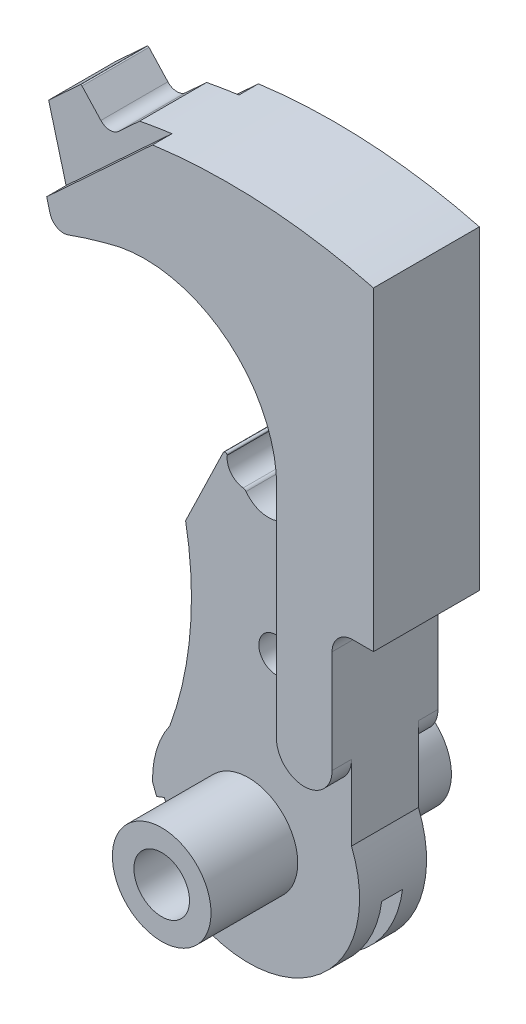
SolidWorks part; units mm, degrees
ref_plane "Front Plane" through (0, 0, 0) normal (0, 0, 1) x (1, 0, 0)
ref_plane "Top Plane" through (0, 0, 0) normal (0, 1, 0) x (1, 0, 0)
ref_plane "Right Plane" through (0, 0, 0) normal (1, 0, 0) x (0, 0, -1)
sketch "Sketch1" plane through (0, 0, 0) normal (0, 0, 1) x (1, 0, 0)
  line L0 (0, 0) -> (-5.4824, 9.4958) construction
  line L1 (0, 0) -> (0, 5.9391)
  line L2 (-5.5315, -2.1233) -> (-7.42, -2.8483)
  line L3 (8, 0) -> (-6.9, 0)
  line L4 (7.42, 9.3953) -> (4.3096, 9.3953)
  line L5 (-5.4824, 9.4958) -> (-12.2807, 5.5708)
  line L6 (0, 0) -> (64.7351, 0) construction
  line L7 (0, 0) -> (-6.9, 0) construction
  line L8 (-12.2807, 5.5708) -> (-7.42, -2.8483) construction
  line L9 (-6.898, -0.168) -> (-6.6058, -0.929)
  line L10 (-7.42, -2.8483) -> (-6.0273, -5.2603)
  line L11 (-6.069, -0.723) -> (-6.6058, -0.929)
  line L12 (-29.5, 0) -> (-29.5, 12.7) construction
  line L13 (-12.463, 0) -> (-29.5, 0) construction
  line L14 (3.439, 22.4832) -> (3.439, 24.0389)
  line L15 (0, 0) -> (55.9226, 51.6581) construction
  line L16 (10.4, 17.3) -> (8.92, 17.3)
  line L17 (-14.3773, 38.5869) -> (-12.8729, 32.9724)
  line L18 (-9.8884, 42.7335) -> (-9.8884, 42.7335)
  line L19 (-6.0367, -0.7373) -> (-5.5171, -2.091)
  line L20 (0, 21.4277) -> (0, 58.1236) construction
  line L21 (76.0334, 0) -> (76.0334, 23)
  line L22 (76.0334, 23) -> (-18.3142, 23) construction
  line L23 (0, -18.7657) -> (0, 8) construction
  line L24 (-28.2689, 25.7547) -> (-25.8525, 27.9867)
  line L25 (10.4, 39.9691) -> (10.4, 17.3)
  line L26 (-39.1696, 36.6554) -> (-18.3142, 15.8)
  line L27 (-9.8884, 42.7335) -> (30.07, 79.6448) construction
  line L28 (-1.8081, 22.9153) -> (-20.4385, -15.63)
  line L29 (7.42, 15.8) -> (7.42, 2.9906)
  line L30 (-1.5211, 22.8792) -> (-1.5371, 22.9134)
  line L31 (-8.4076, 40.0172) -> (-8.4076, 40.0172)
  line L32 (-9.3461, 39.1504) -> (-7.8298, 40.551)
  line L33 (-4.7807, 6.8592) -> (-8.9771, 5.2484)
  line L34 (-7.7738, 38.833) -> (-7.7738, 38.833)
  line L35 (-24.9138, 23) -> (-22.9348, 24.8281)
  line L36 (-8.4076, 40.0172) -> (32.1057, 77.4411) construction
  line L37 (-7.7738, 38.833) -> (32.9878, 76.4862) construction
  line L38 (0, 0) -> (-59.4391, 64.3459) construction
  line L39 (2.9572, 24.505) -> (2.9572, 24.505)
  line L40 (-10.6179, 39.2008) -> (-11.975, 40.6699)
  line L41 (2.9572, 24.505) -> (-45.6294, 77.1025) construction
  line L42 (-14.3773, 38.5869) -> (-12.1163, 40.6755)
  line L43 (182.9929, 126.3651) -> (184.9037, 27.9867)
  arc A0 (-6.0273, -5.2603) -> (7.42, 2.9906) centre (0, 0) ccw
  arc A2 (-5.6516, 3.9584) -> (-4.5206, 17.3032) centre (-29.5, 12.7) ccw
  arc A3 (-5.5315, -2.1233) -> (-5.5171, -2.091) centre (-5.5404, -2.1) ccw
  arc A4 (-6.0367, -0.7373) -> (-6.069, -0.723) centre (-6.0601, -0.7463) ccw
  circle A5 centre (0, 0) radius 2
  arc A6 (-1.5371, 22.9134) -> (-1.8081, 22.9153) centre (-1.673, 22.85) ccw
  arc A8 (-10.6179, 39.2008) -> (-9.3461, 39.1504) centre (-9.9568, 39.8115) ccw
  arc A9 (8.92, 17.3) -> (7.42, 15.8) centre (8.92, 15.8) ccw
  arc A10 (10.4, 39.9691) -> (-7.8298, 40.551) centre (0, 0) ccw
  arc A11 (-7.8825, 33.382) -> (-11.5697, 32.2898) centre (0, 0) ccw
  circle A12 centre (-58.0443, 40.974) radius 9.5
  circle A13 centre (-46.7362, 30.9955) radius 2
  arc A16 (3.439, 24.0389) -> (-7.8825, 33.382) centre (-6.061, 24.0582) ccw
  arc A18 (-1.4991, 23) -> (-0.3776, 21.4148) centre (-0.2326, 22.7067) ccw
  arc A19 (-0.1697, 21.2949) -> (3.439, 22.4832) centre (1.439, 22.4832) ccw
  arc A20 (-0.3776, 21.4148) -> (-0.1697, 21.2949) centre (-0.411, 21.1166) cw
  arc A21 (-11.975, 40.6699) -> (-12.1163, 40.6755) centre (-12.0484, 40.602) ccw
  arc A22 (-5.6516, 3.9584) -> (-6.898, -0.168) centre (0, 0) ccw
  arc A23 (-11.5697, 32.2898) -> (-12.8729, 32.9724) centre (-11.907, 33.2312) cw
  circle A24 centre (163.4559, 87.388) radius 20.2902
  point P48 (-1.553, 23.4431)
  dimension "D1" = 16
  dimension "D8" = 9.3953
  dimension "D12" = 23
  dimension "D10" = 0.025
  dimension "D16" = 0.3
  dimension "D17" = 7.42
  dimension "D15" = 1.5
  dimension "D18" = 34.3
  dimension "D19" = 41.3
  dimension "D24" = 25
  dimension "D25" = 2.6
  dimension "D26" = 0.3
  dimension "D4" = 17.3
  dimension "D9" = 9.5
  dimension "D30" = 0.9
  dimension "D31" = 0.1
  dimension "D32" = 1
  dimension "D2" = 30
  dimension "D3" = 21
  dimension "D5" = 7.85
  dimension "D6" = 17.3
  dimension "D7" = 1.5
  dimension "D11" = 12.7
  dimension "D13" = 0.6
  dimension "D14" = 10.4
  dimension "D20" = 15
  dimension "D21" = 42.73
  dimension "D23" = 35.1
  dimension "D28" = 90
  dimension "D22" = 38.1
  dimension "D27" = 33.8
  dimension "D29" = 18.8
sketch "Sketch6" plane through (0, 0, 0) normal (0, 0, 1) x (1, 0, 0)
  circle A1 centre (2, 12.2) radius 1.25
  dimension "D3" = 2
  dimension "D1" = 2.5
  dimension "D2" = 12.2
sketch "Sketch10" plane through (0, 0, 0) normal (0, 1, 0) x (1, 0, 0)
  circle A0 centre (2, 0) radius 1.5
  dimension "D1" = 2
extrude "Boss-Extrude2" add sketch "Sketch1" along normal mid plane 17.3
ref_plane "Plane1" through (0, 0, 8.65) normal (0, 0, 1) x (1, 0, 0)
sketch "Sketch18" plane through (0, 0, 8.65) normal (0, 0, 1) x (1, 0, 0)
  line L0 (0, 0) -> (-5.4824, 9.4958) construction
  line L1 (0, 0) -> (0, 5.9391)
  line L2 (-5.5315, -2.1233) -> (-7.42, -2.8483)
  line L3 (8, 0) -> (-6.9, 0)
  line L4 (7.42, 9.3953) -> (4.3096, 9.3953)
  line L5 (-5.4824, 9.4958) -> (-12.2807, 5.5708)
  line L6 (0, 0) -> (64.7351, 0) construction
  line L7 (0, 0) -> (-6.9, 0) construction
  line L8 (-12.2807, 5.5708) -> (-7.42, -2.8483) construction
  line L9 (-6.898, -0.168) -> (-6.6058, -0.929)
  line L10 (-7.42, -2.8483) -> (-6.0273, -5.2603)
  line L11 (-6.069, -0.723) -> (-6.6058, -0.929)
  line L12 (-29.5, 0) -> (-29.5, 12.7) construction
  line L13 (-12.463, 0) -> (-29.5, 0) construction
  line L14 (3.439, 22.4832) -> (3.439, 24.0389)
  line L15 (0, 0) -> (55.9226, 51.6581) construction
  line L16 (10.4, 17.3) -> (8.92, 17.3)
  line L17 (-14.3773, 38.5869) -> (-12.8729, 32.9724)
  line L18 (-9.8884, 42.7335) -> (-9.8884, 42.7335)
  line L19 (-6.0367, -0.7373) -> (-5.5171, -2.091)
  line L20 (0, 21.4277) -> (0, 58.1236) construction
  line L21 (76.0334, 0) -> (76.0334, 23)
  line L22 (76.0334, 23) -> (-18.3142, 23) construction
  line L23 (0, -18.7657) -> (0, 8) construction
  line L24 (-28.2689, 25.7547) -> (-25.8525, 27.9867)
  line L25 (10.4, 39.9691) -> (10.4, 17.3)
  line L26 (-39.1696, 36.6554) -> (-18.3142, 15.8)
  line L27 (-9.8884, 42.7335) -> (30.07, 79.6448) construction
  line L28 (-1.8081, 22.9153) -> (-20.4385, -15.63)
  line L29 (7.42, 15.8) -> (7.42, 2.9906)
  line L30 (-1.5211, 22.8792) -> (-1.5371, 22.9134)
  line L31 (-8.4076, 40.0172) -> (-8.4076, 40.0172)
  line L32 (-9.3461, 39.1504) -> (-7.8298, 40.551)
  line L33 (-4.7807, 6.8592) -> (-8.9771, 5.2484)
  line L34 (-7.7738, 38.833) -> (-7.7738, 38.833)
  line L35 (-24.9138, 23) -> (-22.9348, 24.8281)
  line L36 (-8.4076, 40.0172) -> (32.1057, 77.4411) construction
  line L37 (-7.7738, 38.833) -> (32.9878, 76.4862) construction
  line L38 (0, 0) -> (-59.4391, 64.3459) construction
  line L39 (2.9572, 24.505) -> (2.9572, 24.505)
  line L40 (-10.6179, 39.2008) -> (-11.975, 40.6699)
  line L41 (2.9572, 24.505) -> (-45.6294, 77.1025) construction
  line L42 (-14.3773, 38.5869) -> (-12.1163, 40.6755)
  arc A0 (-6.0273, -5.2603) -> (7.42, 2.9906) centre (0, 0) ccw
  arc A2 (-5.6516, 3.9584) -> (-4.5206, 17.3032) centre (-29.5, 12.7) ccw
  arc A3 (-5.5315, -2.1233) -> (-5.5171, -2.091) centre (-5.5404, -2.1) ccw
  arc A4 (-6.0367, -0.7373) -> (-6.069, -0.723) centre (-6.0601, -0.7463) ccw
  circle A5 centre (0, 0) radius 2
  arc A6 (-1.5371, 22.9134) -> (-1.8081, 22.9153) centre (-1.673, 22.85) ccw
  arc A8 (-10.6179, 39.2008) -> (-9.3461, 39.1504) centre (-9.9568, 39.8115) ccw
  arc A9 (8.92, 17.3) -> (7.42, 15.8) centre (8.92, 15.8) ccw
  arc A10 (10.4, 39.9691) -> (-7.8298, 40.551) centre (0, 0) ccw
  arc A11 (-7.8825, 33.382) -> (-11.5697, 32.2898) centre (0, 0) ccw
  circle A12 centre (-58.0443, 40.974) radius 9.5
  circle A13 centre (-46.7362, 30.9955) radius 2
  arc A16 (3.439, 24.0389) -> (-7.8825, 33.382) centre (-6.061, 24.0582) ccw
  arc A18 (-1.4991, 23) -> (-0.3776, 21.4148) centre (-0.2326, 22.7067) ccw
  arc A19 (-0.1697, 21.2949) -> (3.439, 22.4832) centre (1.439, 22.4832) ccw
  arc A20 (-0.3776, 21.4148) -> (-0.1697, 21.2949) centre (-0.411, 21.1166) cw
  arc A21 (-11.975, 40.6699) -> (-12.1163, 40.6755) centre (-12.0484, 40.602) ccw
  arc A22 (-5.6516, 3.9584) -> (-6.898, -0.168) centre (0, 0) ccw
  arc A23 (-11.5697, 32.2898) -> (-12.8729, 32.9724) centre (-11.907, 33.2312) cw
  circle A24 centre (0, 0) radius 3.55
  point P48 (-1.553, 23.4431)
  dimension "D1" = 16
  dimension "D8" = 9.3953
  dimension "D12" = 23
  dimension "D10" = 0.025
  dimension "D16" = 0.3
  dimension "D17" = 7.42
  dimension "D15" = 1.5
  dimension "D18" = 34.3
  dimension "D19" = 41.3
  dimension "D24" = 25
  dimension "D25" = 2.6
  dimension "D26" = 0.3
  dimension "D4" = 17.3
  dimension "D9" = 9.5
  dimension "D30" = 0.9
  dimension "D31" = 0.1
  dimension "D32" = 1
  dimension "D33" = 7.1
  dimension "D2" = 30
  dimension "D3" = 21
  dimension "D5" = 7.85
  dimension "D6" = 17.3
  dimension "D7" = 1.5
  dimension "D11" = 12.7
  dimension "D13" = 0.6
  dimension "D14" = 10.4
  dimension "D20" = 15
  dimension "D21" = 42.73
  dimension "D23" = 35.1
  dimension "D28" = 90
  dimension "D22" = 38.1
  dimension "D27" = 33.8
  dimension "D29" = 18.8
ref_plane "Plane3" through (0, 0, -8.65) normal (0, 0, -1) x (-1, 0, 0)
sketch "Sketch21" plane through (0, 0, -8.65) normal (0, 0, -1) x (-1, 0, 0)
  line L12 (0, 0) -> (59.4391, 64.3459) construction
  line L20 (0, 21.4277) -> (0, 58.1236) construction
  line L21 (0, -18.7657) -> (0, 8) construction
  line L24 (-76.0334, 23) -> (18.3142, 23) construction
  line L26 (0, 0) -> (-55.9226, 51.6581) construction
  line L35 (12.463, 0) -> (29.5, 0) construction
  line L43 (12.2807, 5.5708) -> (7.42, -2.8483) construction
  line L44 (0, 0) -> (6.9, 0) construction
  line L45 (0, 0) -> (-64.7351, 0) construction
  line L46 (0, 0) -> (5.4824, 9.4958) construction
  line L47 (14.3773, 38.5869) -> (12.1163, 40.6755)
  line L48 (10.6179, 39.2008) -> (11.975, 40.6699)
  line L49 (4.7807, 6.8592) -> (8.9771, 5.2484)
  line L50 (9.3461, 39.1504) -> (7.8298, 40.551)
  line L51 (1.5211, 22.8792) -> (1.5371, 22.9134)
  line L52 (-7.42, 15.8) -> (-7.42, 2.9906)
  line L53 (1.8081, 22.9153) -> (20.4385, -15.63)
  line L54 (-10.4, 39.9691) -> (-10.4, 17.3)
  line L55 (6.0367, -0.7373) -> (5.5171, -2.091)
  line L56 (14.3773, 38.5869) -> (12.8729, 32.9724)
  line L57 (-10.4, 17.3) -> (-8.92, 17.3)
  line L58 (-3.439, 22.4832) -> (-3.439, 24.0389)
  line L59 (6.069, -0.723) -> (6.6058, -0.929)
  line L60 (7.42, -2.8483) -> (6.0273, -5.2603)
  line L61 (6.898, -0.168) -> (6.6058, -0.929)
  line L62 (5.4824, 9.4958) -> (12.2807, 5.5708)
  line L63 (-7.42, 9.3953) -> (-4.3096, 9.3953)
  line L64 (-8, 0) -> (6.9, 0)
  line L65 (5.5315, -2.1233) -> (7.42, -2.8483)
  line L66 (0, 0) -> (0, 5.9391)
  circle A3 centre (0, 0) radius 3.55
  circle A5 centre (0, 0) radius 2
  arc A24 (11.5697, 32.2898) -> (12.8729, 32.9724) centre (11.907, 33.2312) ccw
  arc A25 (5.6516, 3.9584) -> (6.898, -0.168) centre (0, 0) cw
  arc A26 (11.975, 40.6699) -> (12.1163, 40.6755) centre (12.0484, 40.602) cw
  arc A27 (0.3776, 21.4148) -> (0.1697, 21.2949) centre (0.411, 21.1166) ccw
  arc A28 (0.1697, 21.2949) -> (-3.439, 22.4832) centre (-1.439, 22.4832) cw
  arc A29 (1.4991, 23) -> (0.3776, 21.4148) centre (0.2326, 22.7067) cw
  arc A30 (-3.439, 24.0389) -> (7.8825, 33.382) centre (6.061, 24.0582) cw
  arc A31 (7.8825, 33.382) -> (11.5697, 32.2898) centre (0, 0) cw
  arc A32 (-10.4, 39.9691) -> (7.8298, 40.551) centre (0, 0) cw
  arc A33 (-8.92, 17.3) -> (-7.42, 15.8) centre (-8.92, 15.8) cw
  arc A34 (10.6179, 39.2008) -> (9.3461, 39.1504) centre (9.9568, 39.8115) cw
  arc A35 (1.5371, 22.9134) -> (1.8081, 22.9153) centre (1.673, 22.85) cw
  arc A36 (6.0367, -0.7373) -> (6.069, -0.723) centre (6.0601, -0.7463) cw
  arc A37 (5.5315, -2.1233) -> (5.5171, -2.091) centre (5.5404, -2.1) cw
  arc A38 (5.6516, 3.9584) -> (4.5206, 17.3032) centre (29.5, 12.7) cw
  arc A39 (6.0273, -5.2603) -> (-7.42, 2.9906) centre (0, 0) cw
  point P44 (1.553, 23.4431)
  dimension "D1" = 7.1
extrude "Cut-Extrude3" cut sketch "Sketch21" against normal blind 4.84
extrude "Cut-Extrude4" cut sketch "Sketch18" against normal blind 4.84
ref_plane "Plane4" through (0, 0, 3.81) normal (0, 0, 1) x (1, 0, 0)
sketch "Sketch27" plane through (0, 0, 3.81) normal (0, 0, 1) x (1, 0, 0)
  line L0 (0, 0) -> (-5.4824, 9.4958) construction
  line L1 (0, 0) -> (0, 5.9391)
  line L2 (-5.5315, -2.1233) -> (-7.42, -2.8483)
  line L3 (8, 0) -> (-6.9, 0)
  line L4 (7.42, 9.3953) -> (4.3096, 9.3953)
  line L5 (-5.4824, 9.4958) -> (-12.2807, 5.5708)
  line L6 (0, 0) -> (64.7351, 0) construction
  line L7 (0, 0) -> (-6.9, 0) construction
  line L8 (-12.2807, 5.5708) -> (-7.42, -2.8483) construction
  line L9 (-6.898, -0.168) -> (-6.6058, -0.929)
  line L10 (-7.42, -2.8483) -> (-6.0273, -5.2603)
  line L11 (-6.069, -0.723) -> (-6.6058, -0.929)
  line L12 (-29.5, 0) -> (-29.5, 12.7) construction
  line L13 (-12.463, 0) -> (-29.5, 0) construction
  line L14 (3.439, 22.4832) -> (3.439, 24.0389)
  line L15 (0, 0) -> (55.9226, 51.6581) construction
  line L16 (10.4, 17.3) -> (8.92, 17.3)
  line L17 (-86.4028, -33.8) -> (42.2343, -33.8)
  line L18 (-6.0367, -0.7373) -> (-5.5171, -2.091)
  line L19 (0, 21.4277) -> (0, 58.1236) construction
  line L20 (76.0334, 0) -> (76.0334, 23)
  line L21 (76.0334, 23) -> (-18.3142, 23) construction
  line L22 (0, -18.7657) -> (0, 8) construction
  line L23 (-28.2689, 25.7547) -> (-25.8525, 27.9867)
  line L24 (10.4, 39.9691) -> (10.4, 17.3)
  line L25 (-39.1696, 36.6554) -> (-18.3142, 15.8)
  line L26 (-1.8081, 22.9153) -> (-20.4385, -15.63)
  line L27 (7.42, 15.8) -> (7.42, 2.9906)
  line L28 (-1.5211, 22.8792) -> (-1.5371, 22.9134)
  line L29 (-9.3461, 39.1504) -> (-7.8298, 40.551)
  line L30 (-4.7807, 6.8592) -> (-8.9771, 5.2484)
  line L31 (-24.9138, 23) -> (-22.9348, 24.8281)
  line L32 (0, 0) -> (-59.4391, 64.3459) construction
  line L33 (-10.6179, 39.2008) -> (-11.975, 40.6699)
  line L34 (-14.3773, 38.5869) -> (-12.1163, 40.6755)
  line L35 (0, 0) -> (42.2343, 0)
  line L36 (7.42, 15.8) -> (7.4024, 8.6651)
  line L37 (0, 0) -> (37.6703, 34.7977)
  line L38 (276.2704, -47.6777) -> (407.1807, -47.6777)
  line L39 (-13.12, 33.8945) -> (-5.5016, 40.9319)
  line L40 (3.42, 8.4) -> (3.42, 24.1192)
  line L41 (-86.4028, -33.8) -> (-22.9348, 24.8281)
  line L42 (10.4, 39.9691) -> (10.4, 17.3)
  line L43 (10.4, 17.3) -> (8.92, 17.3)
  line L44 (-14.3773, 38.5869) -> (-12.8729, 32.9724)
  line L45 (-86.4028, -33.8) -> (14.7355, 59.6258) construction
  arc A0 (-6.0273, -5.2603) -> (7.42, 2.9906) centre (0, 0) ccw
  arc A1 (-5.6516, 3.9584) -> (-4.5206, 17.3032) centre (-29.5, 12.7) ccw
  arc A2 (-5.5315, -2.1233) -> (-5.5171, -2.091) centre (-5.5404, -2.1) ccw
  arc A3 (-6.0367, -0.7373) -> (-6.069, -0.723) centre (-6.0601, -0.7463) ccw
  circle A4 centre (0, 0) radius 2
  arc A5 (-1.5371, 22.9134) -> (-1.8081, 22.9153) centre (-1.673, 22.85) ccw
  arc A6 (-10.6179, 39.2008) -> (-9.3461, 39.1504) centre (-9.9568, 39.8115) ccw
  arc A7 (8.92, 17.3) -> (7.42, 15.8) centre (8.92, 15.8) ccw
  arc A8 (10.4, 39.9691) -> (-7.8298, 40.551) centre (0, 0) ccw
  arc A9 (-7.8825, 33.382) -> (-11.5697, 32.2898) centre (0, 0) ccw
  circle A10 centre (-58.0443, 40.974) radius 9.5
  circle A11 centre (-46.7362, 30.9955) radius 2
  arc A12 (3.439, 24.0389) -> (-7.8825, 33.382) centre (-6.061, 24.0582) ccw
  arc A13 (-1.4991, 23) -> (-0.3776, 21.4148) centre (-0.2326, 22.7067) ccw
  arc A14 (-0.1697, 21.2949) -> (3.439, 22.4832) centre (1.439, 22.4832) ccw
  arc A15 (-0.3776, 21.4148) -> (-0.1697, 21.2949) centre (-0.411, 21.1166) cw
  arc A16 (-11.975, 40.6699) -> (-12.1163, 40.6755) centre (-12.0484, 40.602) ccw
  arc A17 (-5.6516, 3.9584) -> (-6.898, -0.168) centre (0, 0) ccw
  arc A18 (-12.8729, 32.9724) -> (-11.4313, 32.3516) centre (-11.907, 33.2312) ccw
  arc A19 (3.42, 8.4) -> (7.4024, 8.6651) centre (5.42, 8.4) ccw
  arc A20 (3.42, 24.0554) -> (-8.4079, 33.2657) centre (-6.08, 24.0554) ccw
  circle A21 centre (0, 0) radius 3.55
  arc A22 (-8.4079, 33.2657) -> (-11.5728, 32.3013) centre (0, 0) ccw
  arc A23 (10.4, 39.9691) -> (-4.7864, 41.0217) centre (0, 0) ccw
  arc A24 (7.42, 15.8) -> (8.92, 17.3) centre (8.92, 15.8) cw
  point P43 (-1.553, 23.4431)
  dimension "D1" = 42.73
  dimension "D2" = 33.8
extrude "Cut-Extrude7" cut sketch "Sketch27" against normal blind 1.4
ref_plane "Plane5" through (0, 0, -3.81) normal (0, 0, -1) x (-1, 0, 0)
sketch "Sketch29" plane through (0, 0, -3.81) normal (0, 0, -1) x (-1, 0, 0)
  line L19 (0, 21.4277) -> (0, 58.1236) construction
  line L38 (108.7825, -48.9543) -> (239.6927, -48.9543)
  line L45 (0, 0) -> (59.4391, 64.3459) construction
  line L46 (0, -18.7657) -> (0, 8) construction
  line L47 (-76.0334, 23) -> (18.3142, 23) construction
  line L48 (0, 0) -> (-55.9226, 51.6581) construction
  line L49 (12.463, 0) -> (29.5, 0) construction
  line L50 (29.5, 0) -> (29.5, 12.7) construction
  line L51 (12.2807, 5.5708) -> (7.42, -2.8483) construction
  line L52 (0, 0) -> (6.9, 0) construction
  line L53 (0, 0) -> (-64.7351, 0) construction
  line L54 (0, 0) -> (5.4824, 9.4958) construction
  line L55 (14.3773, 38.5869) -> (12.8729, 32.9724)
  line L56 (-10.4, 17.3) -> (-8.92, 17.3)
  line L57 (-10.4, 39.9691) -> (-10.4, 17.3)
  line L58 (86.4028, -33.8) -> (22.9348, 24.8281)
  line L59 (-3.42, 8.4) -> (-3.42, 24.1192)
  line L60 (13.12, 33.8945) -> (5.5016, 40.9319)
  line L61 (0, 0) -> (-37.6703, 34.7977)
  line L62 (-7.42, 15.8) -> (-7.4024, 8.6651)
  line L63 (0, 0) -> (-42.2343, 0)
  line L64 (14.3773, 38.5869) -> (12.1163, 40.6755)
  line L65 (10.6179, 39.2008) -> (11.975, 40.6699)
  line L66 (24.9138, 23) -> (22.9348, 24.8281)
  line L67 (4.7807, 6.8592) -> (8.9771, 5.2484)
  line L68 (9.3461, 39.1504) -> (7.8298, 40.551)
  line L69 (1.5211, 22.8792) -> (1.5371, 22.9134)
  line L70 (-7.42, 15.8) -> (-7.42, 2.9906)
  line L71 (1.8081, 22.9153) -> (20.4385, -15.63)
  line L72 (39.1696, 36.6554) -> (18.3142, 15.8)
  line L73 (-10.4, 39.9691) -> (-10.4, 17.3)
  line L74 (28.2689, 25.7547) -> (25.8525, 27.9867)
  line L75 (-76.0334, 0) -> (-76.0334, 23)
  line L76 (6.0367, -0.7373) -> (5.5171, -2.091)
  line L77 (86.4028, -33.8) -> (-42.2343, -33.8)
  line L78 (-10.4, 17.3) -> (-8.92, 17.3)
  line L79 (-3.439, 22.4832) -> (-3.439, 24.0389)
  line L80 (6.069, -0.723) -> (6.6058, -0.929)
  line L81 (7.42, -2.8483) -> (6.0273, -5.2603)
  line L82 (6.898, -0.168) -> (6.6058, -0.929)
  line L83 (5.4824, 9.4958) -> (12.2807, 5.5708)
  line L84 (-7.42, 9.3953) -> (-4.3096, 9.3953)
  line L85 (-8, 0) -> (6.9, 0)
  line L86 (5.5315, -2.1233) -> (7.42, -2.8483)
  line L87 (0, 0) -> (0, 5.9391)
  circle A4 centre (0, 0) radius 2
  circle A21 centre (0, 0) radius 3.55
  arc A25 (-7.42, 15.8) -> (-8.92, 17.3) centre (-8.92, 15.8) ccw
  arc A26 (-10.4, 39.9691) -> (4.7864, 41.0217) centre (0, 0) cw
  arc A27 (8.4079, 33.2657) -> (11.5728, 32.3013) centre (0, 0) cw
  arc A28 (-3.42, 24.0554) -> (8.4079, 33.2657) centre (6.08, 24.0554) cw
  arc A29 (-3.42, 8.4) -> (-7.4024, 8.6651) centre (-5.42, 8.4) cw
  arc A30 (12.8729, 32.9724) -> (11.4313, 32.3516) centre (11.907, 33.2312) cw
  arc A31 (5.6516, 3.9584) -> (6.898, -0.168) centre (0, 0) cw
  arc A32 (11.975, 40.6699) -> (12.1163, 40.6755) centre (12.0484, 40.602) cw
  arc A33 (0.3776, 21.4148) -> (0.1697, 21.2949) centre (0.411, 21.1166) ccw
  arc A34 (0.1697, 21.2949) -> (-3.439, 22.4832) centre (-1.439, 22.4832) cw
  arc A35 (1.4991, 23) -> (0.3776, 21.4148) centre (0.2326, 22.7067) cw
  arc A36 (-3.439, 24.0389) -> (7.8825, 33.382) centre (6.061, 24.0582) cw
  circle A37 centre (46.7362, 30.9955) radius 2
  circle A38 centre (58.0443, 40.974) radius 9.5
  arc A39 (7.8825, 33.382) -> (11.5697, 32.2898) centre (0, 0) cw
  arc A40 (-10.4, 39.9691) -> (7.8298, 40.551) centre (0, 0) cw
  arc A41 (-8.92, 17.3) -> (-7.42, 15.8) centre (-8.92, 15.8) cw
  arc A42 (10.6179, 39.2008) -> (9.3461, 39.1504) centre (9.9568, 39.8115) cw
  arc A43 (1.5371, 22.9134) -> (1.8081, 22.9153) centre (1.673, 22.85) cw
  arc A44 (6.0367, -0.7373) -> (6.069, -0.723) centre (6.0601, -0.7463) cw
  arc A45 (5.5315, -2.1233) -> (5.5171, -2.091) centre (5.5404, -2.1) cw
  arc A46 (5.6516, 3.9584) -> (4.5206, 17.3032) centre (29.5, 12.7) cw
  arc A47 (6.0273, -5.2603) -> (-7.42, 2.9906) centre (0, 0) cw
  point P251 (1.553, 23.4431)
extrude "Cut-Extrude8" cut sketch "Sketch29" against normal blind 1.4
extrude "Cut-Extrude9" cut sketch "Sketch6" against normal through all both and the other way through all
sketch "Sketch30" plane through (0, 0, 0) normal (0, 0, 1) x (1, 0, 0)
  line L0 (-6.0582, -6.3959) -> (13.8254, 1.2367) construction
  line L1 (-7.42, -2.8483) -> (-7.4686, -2.8669)
  line L4 (-6.0582, -6.3959) -> (7.9341, -1.0247)
  line L5 (-6.0582, -6.3959) -> (-9.3146, -7.6459)
  line L6 (-7.42, -2.8483) -> (-10.6764, -4.0983) construction
  line L9 (-7.42, -2.8483) -> (12.4636, 4.7843) construction
  arc A1 (-5.2105, -6.0705) -> (7.9341, -1.0247) centre (0, 0) ccw
extrude "Cut-Extrude10" cut sketch "Sketch30" against normal mid plane 1.5 contours L4 A1
